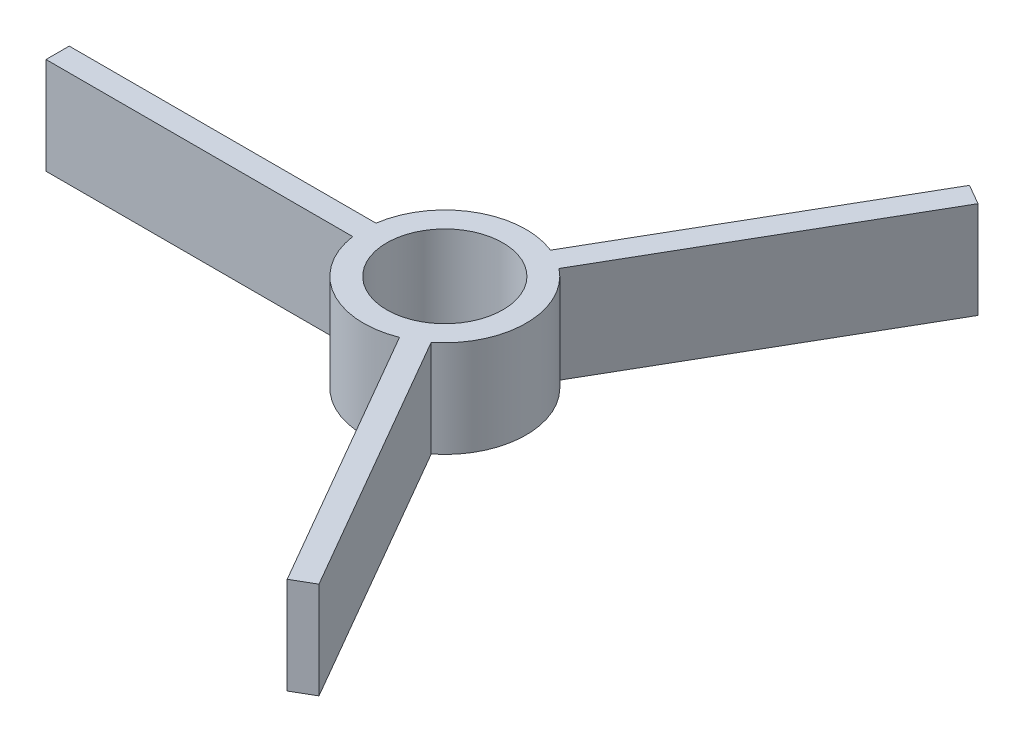
SolidWorks part; units mm, degrees
ref_plane "Front Plane" through (0, 0, 0) normal (0, 0, 1) x (1, 0, 0)
ref_plane "Top Plane" through (0, 0, 0) normal (0, 1, 0) x (1, 0, 0)
ref_plane "Right Plane" through (0, 0, 0) normal (1, 0, 0) x (0, 0, -1)
sketch "Sketch1" plane through (0, 0, 0) normal (0, 1, 0) x (1, 0, 0)
  line L0 (-4.1569, -0.6) -> (-20, -0.6)
  line L2 (-4.1569, 0.6) -> (-20, 0.6)
  line L4 (-20, 0.6) -> (-20, -0.6)
  line L6 (10.5196, 17.0205) -> (9.4804, 17.6205)
  line L7 (2.5981, 3.3) -> (10.5196, 17.0205)
  line L8 (1.5588, 3.9) -> (9.4804, 17.6205)
  line L9 (9.4804, -17.6205) -> (10.5196, -17.0205)
  line L10 (1.5588, -3.9) -> (9.4804, -17.6205)
  line L11 (2.5981, -3.3) -> (10.5196, -17.0205)
  circle A2 centre (0, 0) radius 3
  arc A8 (-4.1569, -0.6) -> (1.5588, -3.9) centre (0, 0) ccw
  arc A9 (1.5588, 3.9) -> (-4.1569, 0.6) centre (0, 0) ccw
  arc A10 (2.5981, -3.3) -> (2.5981, 3.3) centre (0, 0) ccw
  point P17 (0, 0)
  dimension "D1" = 6
  dimension "D6" = 20
  dimension "D2" = 1.2
  dimension "D3" = 0.6
  dimension "D4" = 1.2
  dimension "D5" = 20
  dimension "D7" = 3
extrude "Boss-Extrude2" add sketch "Sketch1" along normal blind 5
